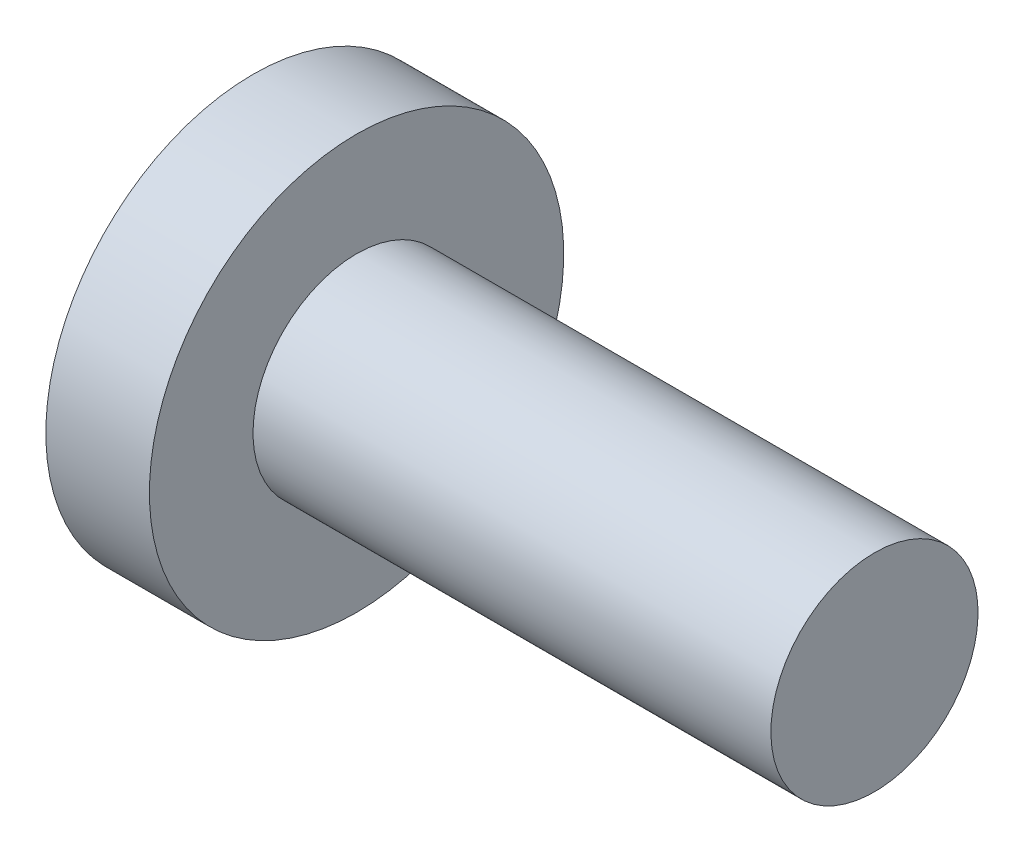
SolidWorks part; units mm, degrees
ref_plane "Front Plane" through (0, 0, 0) normal (0, 0, 1) x (1, 0, 0)
ref_plane "Top Plane" through (0, 0, 0) normal (0, 1, 0) x (1, 0, 0)
ref_plane "Right Plane" through (0, 0, 0) normal (1, 0, 0) x (0, 0, -1)
sketch "Sketch1" plane through (0, 0, 0) normal (0, 0, 1) x (1, 0, 0)
  line L0 (0, 0) -> (1, 0)
  line L1 (1, 0) -> (1, -1)
  line L2 (1, -1) -> (6, -1)
  line L3 (6, -1) -> (6, -2)
  line L4 (6, -2) -> (0, -2)
  line L5 (0, -2) -> (0, 0)
  dimension "D1" = 1
  dimension "D2" = 5
  dimension "D3" = 6
  dimension "D4" = 2
revolve "Revolve1" add sketch "Sketch1" angle 360 about L4
